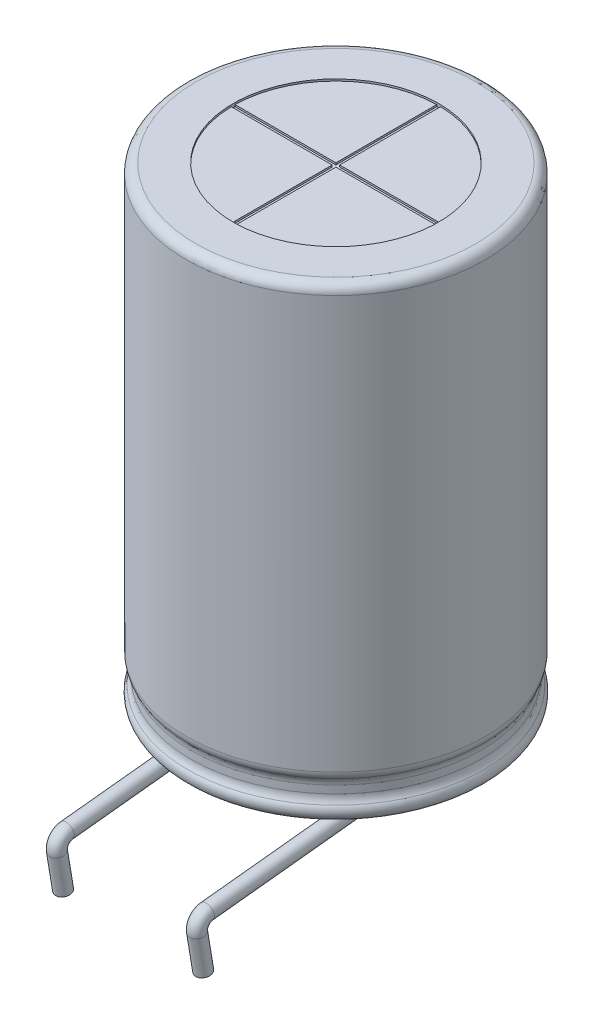
SolidWorks part; units mm, degrees
ref_plane "Front Plane" through (0, 0, 0) normal (0, 0, 1) x (1, 0, 0)
ref_plane "Top Plane" through (0, 0, 0) normal (0, 1, 0) x (1, 0, 0)
ref_plane "Right Plane" through (0, 0, 0) normal (1, 0, 0) x (0, 0, -1)
sketch "Sketch1" plane through (0, 0, 0) normal (0, 0, 1) x (1, 0, 0)
  line L0 (8, 25) -> (0, 25)
  line L1 (0, 25) -> (0, 0)
  line L2 (0, 0) -> (8, 0)
  line L3 (7.7604, 1.2326) -> (7.7604, 1.6424)
  line L4 (8, 2.4076) -> (8, 25)
  line L5 (0, 25) -> (0, 0) construction
  arc A0 (8, 0) -> (7.9281, 0.789) centre (7.4249, 0.3453) ccw
  arc A1 (7.9281, 0.789) -> (7.7604, 1.2326) centre (8.4312, 1.2326) cw
  arc A2 (7.7604, 1.6424) -> (7.8802, 2.025) centre (8.4312, 1.6424) cw
  arc A3 (7.8802, 2.025) -> (8, 2.4076) centre (7.3292, 2.4076) ccw
  dimension "D1" = 25
  dimension "D2" = 8
revolve "Revolve1" add sketch "Sketch1" angle 360 about L5
sketch "Sketch2" plane through (0, 25, 0) normal (0, 1, 0) x (-1, 0, 0)
  circle A0 centre (0, 0) radius 5.5
  dimension "D1" = 11
extrude "Cut-Extrude1" cut sketch "Sketch2" against normal blind 0.1
sketch "Sketch3" plane through (0, 24.9, 0) normal (0, 1, 0) x (-1, 0, 0)
  line L0 (-5.4991, -0.1) -> (-0.1, -0.1)
  line L1 (-0.1, -0.1) -> (-0.1, -5.4991)
  line L2 (-0.1, 5.4991) -> (-0.1, 0.1)
  line L3 (-0.1, 0.1) -> (-5.4991, 0.1)
  line L4 (5.4991, 0.1) -> (0.1, 0.1)
  line L5 (0.1, 0.1) -> (0.1, 5.4991)
  line L6 (0.1, -5.4991) -> (0.1, -0.1)
  line L7 (0.1, -0.1) -> (5.4991, -0.1)
  line L9 (0, 6.2081) -> (0, -6.5499) construction
  line L10 (6.8771, 0) -> (-11.2847, 0) construction
  circle A0 centre (0, 0) radius 5.5 construction
  arc A1 (-5.5, 0) -> (-5.4991, -0.1) centre (0, 0) ccw
  arc A2 (-0.1, -5.4991) -> (0, -5.5) centre (0, 0) ccw
  arc A3 (0, 5.5) -> (-0.1, 5.4991) centre (0, 0) ccw
  arc A4 (-5.4991, 0.1) -> (-5.5, 0) centre (0, 0) ccw
  arc A5 (5.5, 0) -> (5.4991, 0.1) centre (0, 0) ccw
  arc A6 (0.1, 5.4991) -> (0, 5.5) centre (0, 0) ccw
  arc A7 (0, -5.5) -> (0.1, -5.4991) centre (0, 0) ccw
  arc A8 (5.4991, -0.1) -> (5.5, 0) centre (0, 0) ccw
  dimension "D1" = 0.1
  dimension "D2" = 0.1
  dimension "D3" = 4
extrude "Cut-Extrude2" cut sketch "Sketch3" against normal blind 0.1
sketch "Croquis4" plane through (0, 0, 0) normal (0, -1, 0) x (1, 0, 0)
  circle A0 centre (0, 0) radius 5.5
  dimension "D1" = 11
extrude "Cortar-Extruir1" cut sketch "Croquis4" against normal blind 0.25
ref_plane "Plano1" through (3.75, 0, 0) normal (1, 0, 0) x (0, 0, -1)
sketch "Croquis2" plane through (3.75, 0, 0) normal (1, 0, 0) x (0, 0, -1)
  line L0 (0, 0.25) -> (0, 0)
  line L1 (-1.3403, -1.4915) -> (-10.6511, -2.4882)
  line L2 (-11.1791, -3.1833) -> (-10.8509, -5.1562)
  arc A0 (0, 0) -> (-1.3403, -1.4915) centre (-1.5, 0) cw
  arc A1 (-11.1791, -3.1833) -> (-10.6511, -2.4882) centre (-10.5873, -3.0848) cw
  point P7 (-11.2835, -2.5559)
  point P8 (0, 0)
  point P9 (0, 0)
  point P10 (0, 0)
  point P11 (0, 0)
  point P12 (-9.493, -8.0449)
  dimension "D1" = 1.5
  dimension "D4" = 0.6
  dimension "D2" = 0.25
  dimension "D3" = 10
  dimension "D5" = 2
sketch "Croquis8" plane through (0, 0.25, 0) normal (0, -1, 0) x (1, 0, 0)
  line L0 (3.75, 0) -> (3.75, 1.3403) construction
  circle A0 centre (3.75, 0) radius 0.4
  dimension "D1" = 0.8
fillet "Fillet1" radius 0.5 2 edges at (8, 25, 0) (8, 0, 0)
ref_plane "Plano2" through (-3.75, 0, 0) normal (1, 0, 0) x (0, 0, -1)
sketch "Croquis6" plane through (-3.75, 0, 0) normal (1, 0, 0) x (0, 0, -1)
  line L0 (0.0523, 0.25) -> (0.0523, 0)
  line L1 (-1.4477, -1.5) -> (-11.4477, -1.5)
  line L2 (-5.5, 0.25) -> (5.5, 0.25) construction
  arc A0 (0.0523, 0) -> (-1.4477, -1.5) centre (-1.4477, 0) cw
  dimension "D1" = 1.5
  dimension "D2" = 0.25
  dimension "D3" = 10
sketch "Croquis7" plane through (0, 0.25, 0) normal (0, -1, 0) x (1, 0, 0)
  line L0 (-3.75, -0.0523) -> (-3.75, 1.4477) construction
  circle A0 centre (-3.75, -0.0523) radius 0.4
  dimension "D1" = 0.8
sweep "Barrer6" add profiles "Croquis8" path "Croquis2"
mirror "Mirror1" about plane through (0, 0, 0) normal (1, 0, 0) of "Barrer6"
